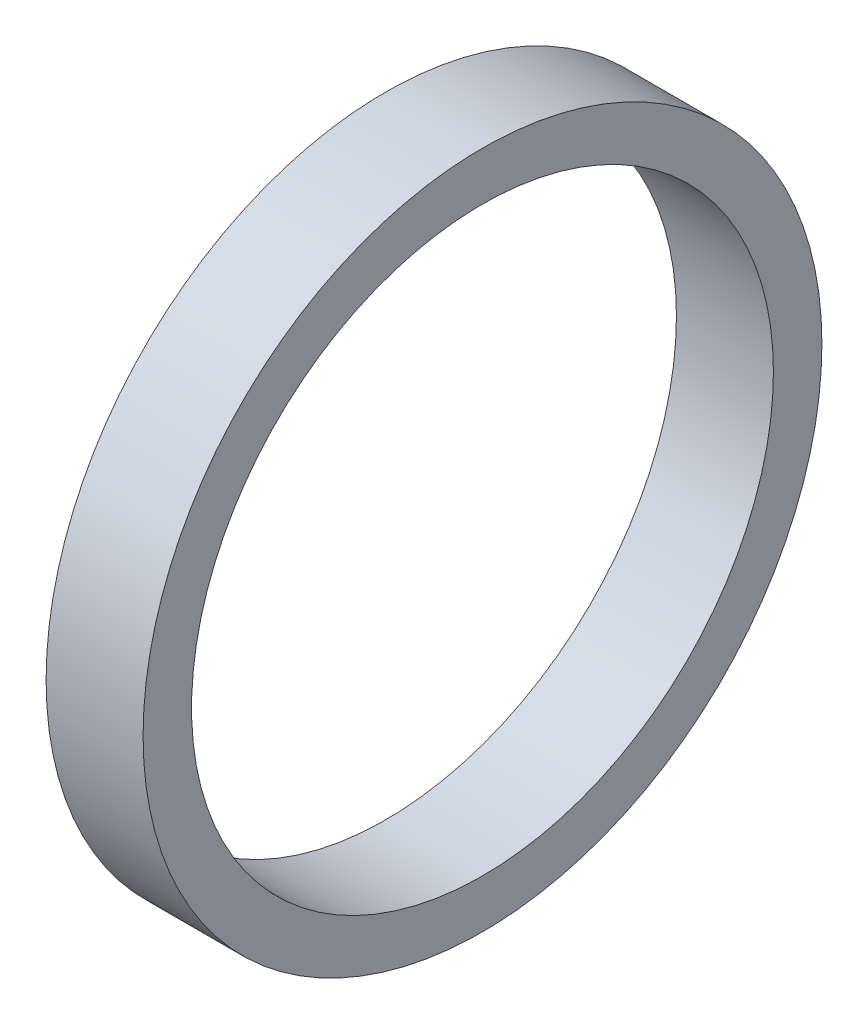
SolidWorks part; units mm, degrees
ref_plane "前视基准面" through (0, 0, 0) normal (0, 0, 1) x (1, 0, 0)
ref_plane "上视基准面" through (0, 0, 0) normal (0, 1, 0) x (1, 0, 0)
ref_plane "右视基准面" through (0, 0, 0) normal (1, 0, 0) x (0, 0, -1)
sketch "草图1" plane through (0, 0, 0) normal (1, 0, 0) x (0, 0, -1)
  circle A0 centre (0, 0) radius 3
  circle A1 centre (0, 0) radius 3.5
extrude "凸台-拉伸1" add sketch "草图1" along normal blind 1
